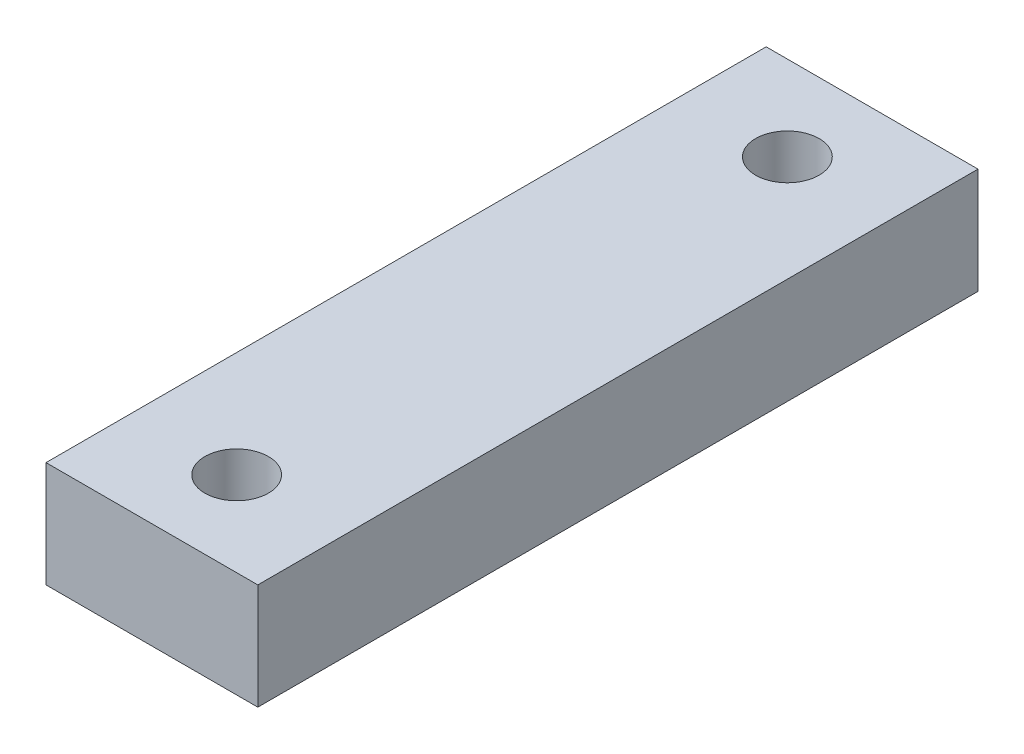
SolidWorks part; units mm, degrees
ref_plane "Front Plane" through (0, 0, 0) normal (0, 0, 1) x (1, 0, 0)
ref_plane "Top Plane" through (0, 0, 0) normal (0, 1, 0) x (1, 0, 0)
ref_plane "Right Plane" through (0, 0, 0) normal (1, 0, 0) x (0, 0, -1)
sketch "Sketch1" plane through (0, 0, 0) normal (0, 0, 1) x (1, 0, 0)
  line L1 (0, 0) -> (50, 0)
  line L2 (0, 0) -> (0, -25)
  line L3 (0, -25) -> (50, -25)
  line L4 (50, 0) -> (50, -25)
  dimension "D1" = 25
  dimension "D2" = 50
extrude "Boss-Extrude1" add sketch "Sketch1" along normal blind 170
sketch "Sketch2" plane through (0, 0, 0) normal (0, 1, 0) x (1, 0, 0)
  line L0 (0, -170) -> (0, 0) construction
  line L2 (50, 0) -> (0, 0) construction
  circle A0 centre (25, -20) radius 7.5
  point P6 (20.7025, 0)
  dimension "D1" = 25
  dimension "D2" = 20
extrude "Cut-Extrude1" cut sketch "Sketch2" against normal through all
sketch "Sketch3" plane through (0, 0, 0) normal (0, 1, 0) x (1, 0, 0)
  line L0 (50, -170) -> (50, 0) construction
  line L2 (50, -170) -> (0, -170) construction
  circle A0 centre (25, -150) radius 7.5
  point P6 (30.5868, -170)
  dimension "D1" = 25
  dimension "D2" = 20
extrude "Cut-Extrude2" cut sketch "Sketch3" against normal blind 170
